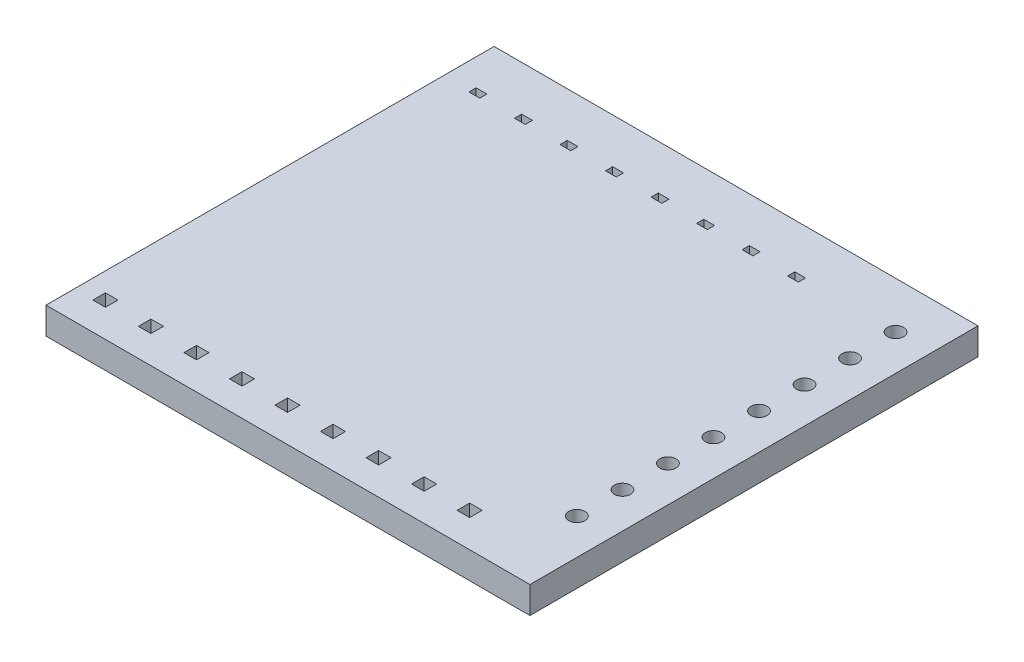
SolidWorks part; units mm, degrees
ref_plane "Front" through (0, 0, 0) normal (0, 0, 1) x (1, 0, 0)
ref_plane "Top" through (0, 0, 0) normal (0, 1, 0) x (1, 0, 0)
ref_plane "Right" through (0, 0, 0) normal (1, 0, 0) x (0, 0, -1)
sketch "Эскиз1" plane through (0, 0, 0) normal (0, 1, 0) x (1, 0, 0)
  line L1 (-13.5, 12.5) -> (13.5, 12.5)
  line L2 (-13.5, 12.5) -> (-13.5, -12.5)
  line L3 (-13.5, -12.5) -> (13.5, -12.5)
  line L4 (13.5, 12.5) -> (13.5, -12.5)
  line L5 (-13.5, 12.5) -> (13.5, -12.5) construction
  line L6 (-13.5, -12.5) -> (13.5, 12.5) construction
  point P0 (0, 0)
extrude "Бобышка-Вытянуть1" add sketch "Эскиз1" along normal blind 1.5
sketch "Эскиз2" plane through (0, 1.5, 0) normal (0, 1, 0) x (1, 0, 0)
  line L0 (-13.5, 12.5) -> (-13.5, 9.8) construction
  line L1 (-13.5, 12.5) -> (-13.5, -12.5) construction
  line L2 (-13.5, 9.8) -> (-11.7, 9.8) construction
  line L3 (-9.46, 10) -> (-8.86, 10)
  line L4 (-9.46, 10) -> (-9.46, 9.6)
  line L5 (-12, 10) -> (-11.4, 10)
  line L6 (-12, 10) -> (-12, 9.6)
  line L7 (-12, 9.6) -> (-11.4, 9.6)
  line L8 (-11.4, 10) -> (-11.4, 9.6)
  line L9 (-12, 10) -> (-11.4, 9.6) construction
  line L10 (-9.46, 9.6) -> (-8.86, 9.6)
  line L11 (-8.86, 10) -> (-8.86, 9.6)
  line L12 (-9.46, 10) -> (-8.86, 9.6) construction
  line L13 (-9.46, 9.6) -> (-8.86, 10) construction
  line L14 (-6.92, 10) -> (-6.32, 10)
  line L15 (-6.92, 10) -> (-6.92, 9.6)
  line L16 (-6.92, 9.6) -> (-6.32, 9.6)
  line L17 (-6.32, 10) -> (-6.32, 9.6)
  line L18 (-6.92, 10) -> (-6.32, 9.6) construction
  line L19 (-6.92, 9.6) -> (-6.32, 10) construction
  line L20 (-4.38, 10) -> (-3.78, 10)
  line L21 (-4.38, 10) -> (-4.38, 9.6)
  line L22 (-4.38, 9.6) -> (-3.78, 9.6)
  line L23 (-3.78, 10) -> (-3.78, 9.6)
  line L24 (-4.38, 10) -> (-3.78, 9.6) construction
  line L25 (-4.38, 9.6) -> (-3.78, 10) construction
  line L26 (-1.84, 10) -> (-1.24, 10)
  line L27 (-1.84, 10) -> (-1.84, 9.6)
  line L28 (-1.84, 9.6) -> (-1.24, 9.6)
  line L29 (-1.24, 10) -> (-1.24, 9.6)
  line L30 (-1.84, 10) -> (-1.24, 9.6) construction
  line L31 (-1.84, 9.6) -> (-1.24, 10) construction
  line L32 (0.7, 10) -> (1.3, 10)
  line L33 (0.7, 10) -> (0.7, 9.6)
  line L34 (0.7, 9.6) -> (1.3, 9.6)
  line L35 (1.3, 10) -> (1.3, 9.6)
  line L36 (0.7, 10) -> (1.3, 9.6) construction
  line L37 (0.7, 9.6) -> (1.3, 10) construction
  line L38 (3.24, 10) -> (3.84, 10)
  line L39 (3.24, 10) -> (3.24, 9.6)
  line L40 (3.24, 9.6) -> (3.84, 9.6)
  line L41 (3.84, 10) -> (3.84, 9.6)
  line L42 (3.24, 10) -> (3.84, 9.6) construction
  line L43 (3.24, 9.6) -> (3.84, 10) construction
  line L44 (5.78, 10) -> (6.38, 10)
  line L45 (5.78, 10) -> (5.78, 9.6)
  line L46 (5.78, 9.6) -> (6.38, 9.6)
  line L47 (6.38, 10) -> (6.38, 9.6)
  line L48 (5.78, 10) -> (6.38, 9.6) construction
  line L49 (5.78, 9.6) -> (6.38, 10) construction
  line L50 (13.5, 12.5) -> (13.5, 9.9) construction
  line L51 (-12, 9.6) -> (-11.4, 10) construction
  line L52 (13.5, -12.5) -> (13.5, 12.5) construction
  line L53 (13.5, 9.9) -> (11.5, 9.9) construction
  line L54 (-9.8979, -10.2464) -> (-9.1979, -10.2464)
  line L55 (-9.8979, -10.2464) -> (-9.8979, -10.9464)
  line L56 (-9.8979, -10.9464) -> (-9.1979, -10.9464)
  line L57 (-9.1979, -10.2464) -> (-9.1979, -10.9464)
  line L58 (-9.8979, -10.2464) -> (-9.1979, -10.9464) construction
  line L59 (-9.8979, -10.9464) -> (-9.1979, -10.2464) construction
  line L60 (-7.3579, -10.2464) -> (-6.6579, -10.2464)
  line L61 (-7.3579, -10.2464) -> (-7.3579, -10.9464)
  line L62 (-7.3579, -10.9464) -> (-6.6579, -10.9464)
  line L63 (-6.6579, -10.2464) -> (-6.6579, -10.9464)
  line L64 (-7.3579, -10.2464) -> (-6.6579, -10.9464) construction
  line L65 (-7.3579, -10.9464) -> (-6.6579, -10.2464) construction
  line L66 (-4.8179, -10.2464) -> (-4.1179, -10.2464)
  line L67 (-4.8179, -10.2464) -> (-4.8179, -10.9464)
  line L68 (-4.8179, -10.9464) -> (-4.1179, -10.9464)
  line L69 (-4.1179, -10.2464) -> (-4.1179, -10.9464)
  line L70 (-4.8179, -10.2464) -> (-4.1179, -10.9464) construction
  line L71 (-4.8179, -10.9464) -> (-4.1179, -10.2464) construction
  line L72 (-2.2779, -10.2464) -> (-1.5779, -10.2464)
  line L73 (-2.2779, -10.2464) -> (-2.2779, -10.9464)
  line L74 (-2.2779, -10.9464) -> (-1.5779, -10.9464)
  line L75 (-1.5779, -10.2464) -> (-1.5779, -10.9464)
  line L76 (-2.2779, -10.2464) -> (-1.5779, -10.9464) construction
  line L77 (-2.2779, -10.9464) -> (-1.5779, -10.2464) construction
  line L78 (0.2621, -10.2464) -> (0.9621, -10.2464)
  line L79 (0.2621, -10.2464) -> (0.2621, -10.9464)
  line L80 (0.2621, -10.9464) -> (0.9621, -10.9464)
  line L81 (0.9621, -10.2464) -> (0.9621, -10.9464)
  line L82 (0.2621, -10.2464) -> (0.9621, -10.9464) construction
  line L83 (0.2621, -10.9464) -> (0.9621, -10.2464) construction
  line L84 (2.8021, -10.2464) -> (3.5021, -10.2464)
  line L85 (2.8021, -10.2464) -> (2.8021, -10.9464)
  line L86 (2.8021, -10.9464) -> (3.5021, -10.9464)
  line L87 (3.5021, -10.2464) -> (3.5021, -10.9464)
  line L88 (2.8021, -10.2464) -> (3.5021, -10.9464) construction
  line L89 (2.8021, -10.9464) -> (3.5021, -10.2464) construction
  line L90 (5.3421, -10.2464) -> (6.0421, -10.2464)
  line L91 (5.3421, -10.2464) -> (5.3421, -10.9464)
  line L92 (5.3421, -10.9464) -> (6.0421, -10.9464)
  line L93 (6.0421, -10.2464) -> (6.0421, -10.9464)
  line L94 (5.3421, -10.2464) -> (6.0421, -10.9464) construction
  line L95 (5.3421, -10.9464) -> (6.0421, -10.2464) construction
  line L96 (7.8821, -10.2464) -> (8.5821, -10.2464)
  line L97 (7.8821, -10.2464) -> (7.8821, -10.9464)
  line L98 (7.8821, -10.9464) -> (8.5821, -10.9464)
  line L99 (8.5821, -10.2464) -> (8.5821, -10.9464)
  line L100 (7.8821, -10.2464) -> (8.5821, -10.9464) construction
  line L101 (7.8821, -10.9464) -> (8.5821, -10.2464) construction
  line L102 (-13.5, -12.5) -> (-12.0879, -12.5) construction
  line L103 (-13.5, -12.5) -> (13.5, -12.5) construction
  line L104 (-12.0879, -12.5) -> (-12.0879, -10.5964) construction
  line L112 (-12.4379, -10.2464) -> (-11.7379, -10.2464)
  line L113 (-12.4379, -10.2464) -> (-12.4379, -10.9464)
  line L114 (-12.4379, -10.9464) -> (-11.7379, -10.9464)
  line L115 (-11.7379, -10.2464) -> (-11.7379, -10.9464)
  line L116 (-12.4379, -10.2464) -> (-11.7379, -10.9464) construction
  line L117 (-12.4379, -10.9464) -> (-11.7379, -10.2464) construction
  circle A0 centre (11.5, 9.9) radius 0.45
  circle A1 centre (11.5, 7.36) radius 0.45
  circle A2 centre (11.5, 4.82) radius 0.45
  circle A3 centre (11.5, 2.28) radius 0.45
  circle A4 centre (11.5, -0.26) radius 0.45
  circle A5 centre (11.5, -2.8) radius 0.45
  circle A6 centre (11.5, -5.34) radius 0.45
  circle A7 centre (11.5, -7.88) radius 0.45
  dimension "D1" = 8
  dimension "D2" = 8
  dimension "D3" = 9
extrude "Вырез-Вытянуть1" cut sketch "Эскиз2" against normal through all
